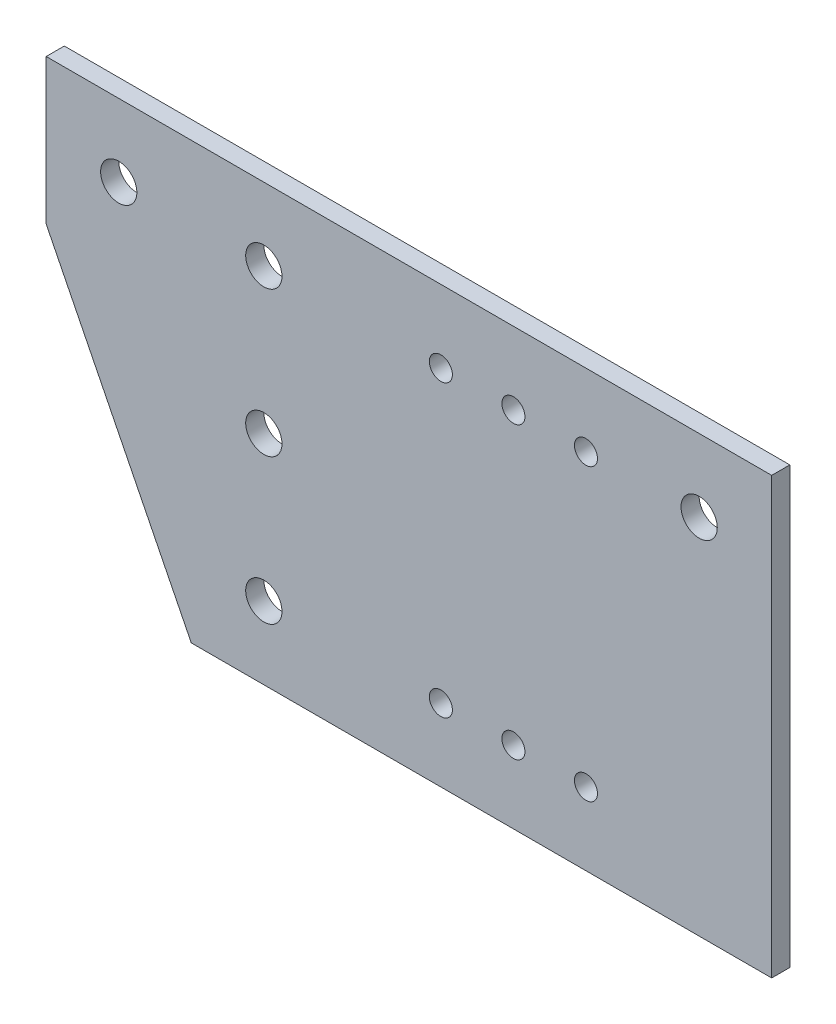
SolidWorks part; units mm, degrees
ref_plane "Front Plane" through (0, 0, 0) normal (0, 0, 1) x (1, 0, 0)
ref_plane "Top Plane" through (0, 0, 0) normal (0, 1, 0) x (1, 0, 0)
ref_plane "Right Plane" through (0, 0, 0) normal (1, 0, 0) x (0, 0, -1)
sketch "Sketch4" plane through (0, 0, 0) normal (0, 0, 1) x (1, 0, 0)
  line L6 (-38.1, 12.7) -> (88.9, 12.7)
  line L7 (88.9, 12.7) -> (88.9, -12.7)
  line L9 (-38.1, 12.7) -> (-38.1, -12.7)
  line L10 (-38.1, -12.7) -> (-12.7, -63.5)
  line L11 (-12.7, -63.5) -> (12.7, -63.5)
  line L12 (50.8, 0) -> (25.4, 0) construction
  line L13 (25.4, 0) -> (0, 0) construction
  line L14 (0, 0) -> (-25.4, 0) construction
  line L15 (50.8, 0) -> (76.2, 0) construction
  line L16 (0, 0) -> (0, -25.4) construction
  line L17 (0, -25.4) -> (0, -50.8) construction
  line L18 (0, -63.5) -> (0, -50.8) construction
  line L19 (88.9, -12.7) -> (88.9, -63.5)
  line L20 (88.9, -63.5) -> (12.7, -63.5)
  circle A1 centre (-25.4, 0) radius 3.175
  circle A2 centre (0, 0) radius 3.175
  circle A3 centre (25.4, 0) radius 3.175 construction
  circle A4 centre (50.8, 0) radius 3.175 construction
  circle A5 centre (0, -25.4) radius 3.175
  circle A6 centre (0, -50.8) radius 3.175
  circle A7 centre (76.2, 0) radius 3.175
  point P21 (0, -63.5)
  dimension "D2" = 6.35
  dimension "D3" = 6.35
  dimension "D4" = 6.35
  dimension "D5" = 6.35
  dimension "D6" = 6.35
  dimension "D7" = 6.35
  dimension "D8" = 25.4
  dimension "D9" = 25.4
  dimension "D10" = 25.4
  dimension "D11" = 25.4
  dimension "D12" = 25.4
  dimension "D13" = 12.7
  dimension "D14" = 12.7
  dimension "D15" = 6.35
  dimension "D16" = 25.4
  dimension "D17" = 12.7
  dimension "D18" = 25.4
  dimension "D19" = 25.4
  dimension "D20" = 12.7
extrude "Boss-Extrude1" add sketch "Sketch4" along normal blind 3.175
sketch "Sketch7" plane through (0, 0, 3.175) normal (0, 0, 1) x (1, 0, 0)
  line L0 (-38.1, 12.7) -> (-38.1, -12.7)
  line L1 (-38.1, 12.7) -> (-38.1, -12.7) construction
  line L2 (56.388, 0) -> (56.388, -50.8)
  line L3 (-38.1, 12.7) -> (-38.1, 0)
  line L4 (56.388, -50.8) -> (43.688, -50.8)
  line L5 (43.688, -50.8) -> (30.988, -50.8)
  circle A0 centre (30.988, 0) radius 2.0193
  circle A1 centre (43.688, 0) radius 2.0193
  circle A2 centre (56.388, 0) radius 2.0193
  circle A3 centre (56.388, -50.8) radius 2.0193
  circle A4 centre (43.688, -50.8) radius 2.0193
  circle A5 centre (30.988, -50.8) radius 2.0193
  dimension "D3" = 4.0386
  dimension "D5" = 4.0386
  dimension "D7" = 4.0386
  dimension "D2" = 4.0386
  dimension "D9" = 4.0386
  dimension "D11" = 4.0386
  dimension "D1" = 50.8
  dimension "D4" = 12.7
  dimension "D6" = 12.7
  dimension "D8" = 12.7
  dimension "D10" = 12.7
extrude "Cut-Extrude4" cut sketch "Sketch7" against normal blind 5.08
